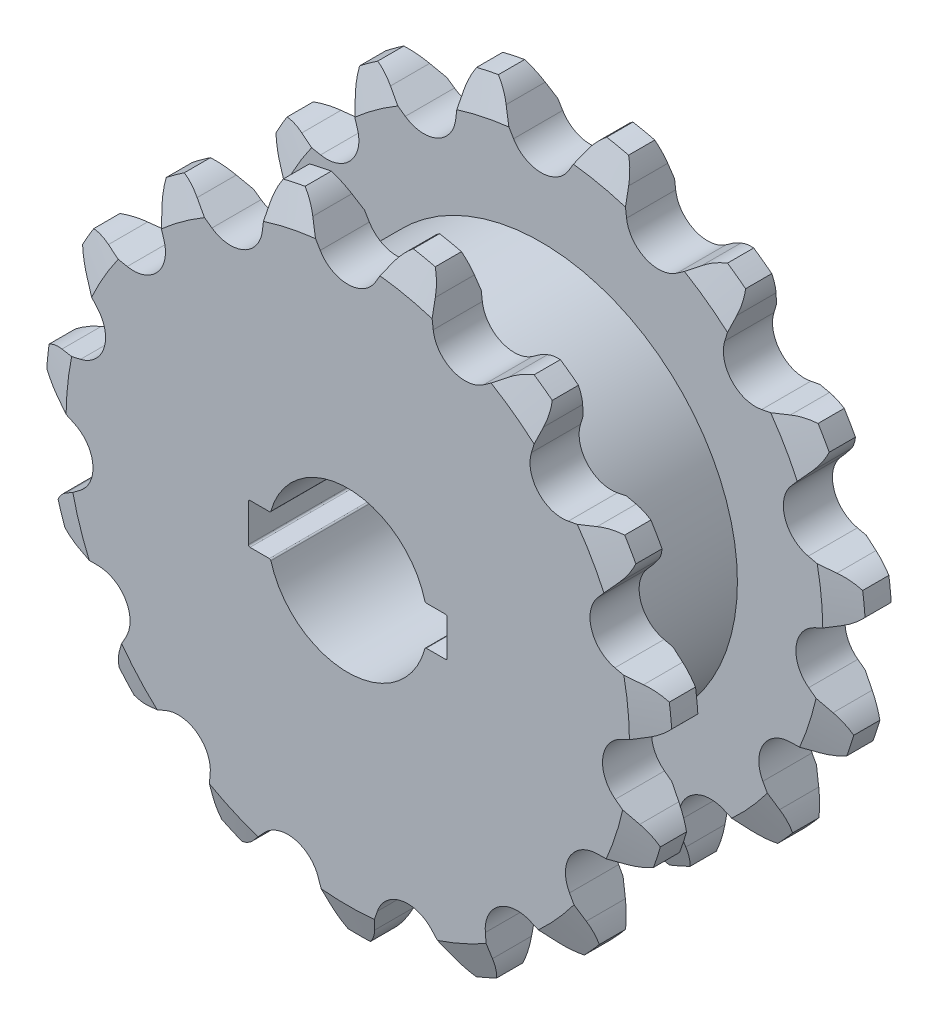
SolidWorks part; units mm, degrees
material "6061-T6 (SS)"
ref_plane "Front Plane" through (0, 0, 0) normal (0, 0, 1) x (1, 0, 0)
ref_plane "Top Plane" through (0, 0, 0) normal (0, 1, 0) x (1, 0, 0)
ref_plane "Right Plane" through (0, 0, 0) normal (1, 0, 0) x (0, 0, -1)
ref_plane "Plane1" through (0, 0, 5.8166) normal (0, 0, 1) x (1, 0, 0)
sketch "Sketch1" plane through (0, 0, 5.8166) normal (0, 0, 1) x (1, 0, 0)
  line L0 (0, 76.6001) -> (0, -76.6001) construction
  line L1 (-124.3299, 0) -> (133.2713, 0) construction
  line L2 (6.2434, 1.5748) -> (8.0137, 1.5748)
  line L3 (8.0137, 1.5748) -> (8.0137, -1.5748)
  line L4 (8.0137, -1.5748) -> (6.2434, -1.5748)
  line L5 (-6.227, 1.6383) -> (-8.0137, 1.6383)
  line L6 (-8.0137, 1.6383) -> (-8.0137, -1.6383)
  line L7 (-8.0137, -1.6383) -> (-6.227, -1.6383)
  arc A0 (-6.227, -1.6383) -> (6.2434, -1.5748) centre (0, 0) ccw
  circle A1 centre (0, 0) radius 25.2603
  arc A2 (6.2434, 1.5748) -> (-6.227, 1.6383) centre (0, 0) ccw
  dimension "D1" = 12.8778
  dimension "D2" = 50.5206
  dimension "D3" = 3.1496
  dimension "D4" = 3.2766
  dimension "D5" = 16.0274
extrude "Extrude1" add sketch "Sketch1" along normal blind 3.9624
sketch "Sketch2" plane through (0, 0, 5.8166) normal (0, 0, -1) x (-1, 0, 0)
  line L6 (8.0137, 1.6383) -> (6.227, 1.6383)
  line L7 (8.0137, -1.6383) -> (8.0137, 1.6383)
  line L8 (6.227, -1.6383) -> (8.0137, -1.6383)
  line L9 (-8.0137, -1.5748) -> (-6.2434, -1.5748)
  line L10 (-8.0137, 1.5748) -> (-8.0137, -1.5748)
  line L11 (-6.2434, 1.5748) -> (-8.0137, 1.5748)
  line L12 (8.0137, 1.6383) -> (6.227, 1.6383)
  line L13 (8.0137, -1.6383) -> (8.0137, 1.6383)
  line L14 (6.227, -1.6383) -> (8.0137, -1.6383)
  line L15 (-8.0137, -1.5748) -> (-6.2434, -1.5748)
  line L16 (-8.0137, 1.5748) -> (-8.0137, -1.5748)
  line L17 (-6.2434, 1.5748) -> (-8.0137, 1.5748)
  circle A0 centre (0, 0) radius 15.8337
  arc A3 (6.227, 1.6383) -> (-6.2434, 1.5748) centre (0, 0) ccw
  arc A4 (-6.2434, -1.5748) -> (6.227, -1.6383) centre (0, 0) ccw
  arc A5 (6.227, 1.6383) -> (-6.2434, 1.5748) centre (0, 0) ccw
  arc A6 (-6.2434, -1.5748) -> (6.227, -1.6383) centre (0, 0) ccw
  dimension "D1" = 31.6673
  dimension "D2" = 0
extrude "Extrude2" add sketch "Sketch2" along normal blind 11.6332
mirror "Mirror5" about plane through (0, 0, 0) normal (0, 0, 1) of "Extrude1"
sketch "Sketch3" plane through (0, 0, 9.779) normal (0, 0, 1) x (1, 0, 0)
  line L0 (0, 25.2603) -> (0, -25.2603) construction
  line L1 (-25.2603, 0) -> (25.2603, 0) construction
  line L2 (2.2225, 21.936) -> (2.6028, 22.5707)
  line L3 (-2.6028, 22.5707) -> (-2.2225, 21.936)
  line L4 (-2.6028, 22.5707) -> (-3.2258, 23.6107)
  line L5 (3.2258, 23.6107) -> (2.6028, 22.5707)
  circle A0 centre (0, 0) radius 25.2603 construction
  arc A1 (-25.2603, 0) -> (25.2603, 0) centre (0, 0) ccw
  arc A2 (-2.2225, 21.936) -> (2.2225, 21.936) centre (0, 23.2674) ccw
  arc A3 (-3.2258, 23.6107) -> (-4.3664, 24.8801) centre (-6.9446, 21.4163) ccw
  arc A4 (4.3664, 24.8801) -> (3.2258, 23.6107) centre (6.9446, 21.4163) ccw
  arc A5 (4.3664, 24.8801) -> (-4.3664, 24.8801) centre (0, 0) ccw
  point P10 (0, 20.6766)
  circle M8 centre (0, 0) radius 25.2603
  dimension "D1" = 2.5908
  dimension "D4" = 4.318
  dimension "D6" = 6.4516
  dimension "D2" = 20.6766
  dimension "D3" = 8.7327
  dimension "D5" = 5.2055
  dimension "D7" = 2.9341
  dimension "D8" = 1.8941
  dimension "D9" = 4.445
extrude "Extrude3" cut sketch "Sketch3" against normal up to surface (19.558 mm away) contours A4 A3 L4 L3 A2 L2 L5 M8
chamfer "Chamfer1" distance 0.9245 distance2 2.54 2 edges at (0, -25.2603, 9.779) (0, -25.2603, -5.8166)
chamfer "Chamfer2" distance 2.54 distance2 0.9245 2 edges at (0, -25.2603, 5.8166) (0, -25.2603, -9.779)
pattern_circular "CirPattern1" count 15 over 360 about axis through (0, 0, 0) along (0, 0, 1) of "Extrude3"
fillet "Fillet1" radius 0.127 8 edges at (8.0137, -1.5748, 0) (8.0137, 1.5748, 0) (-8.0137, 1.6383, 0) (-8.0137, -1.6383, 0) (6.2434, 1.5748, 0) (6.2434, -1.5748, 0) (-6.227, -1.6383, 0) (-6.227, 1.6383, 0)
ref_plane "Plane2" through (0, 0, 7.7978) normal (0, 0, 1) x (1, 0, 0)
ref_plane "Plane3" through (0, 0, -7.7978) normal (0, 0, -1) x (-1, 0, 0)
sketch "Sketch4" plane through (0, 0, 7.7978) normal (0, 0, 1) x (1, 0, 0)
  circle A0 centre (0, 0) radius 22.7203
  arc A1 (15.0317, 17.037) -> (11.5581, 19.5607) centre (0, 0) ccw construction
sketch "Sketch5" plane through (0, 0, -7.7978) normal (0, 0, -1) x (-1, 0, 0)
  circle A0 centre (0, 0) radius 22.7203
  arc A1 (20.6617, 9.4501) -> (18.5149, 13.1685) centre (0, 0) ccw construction
